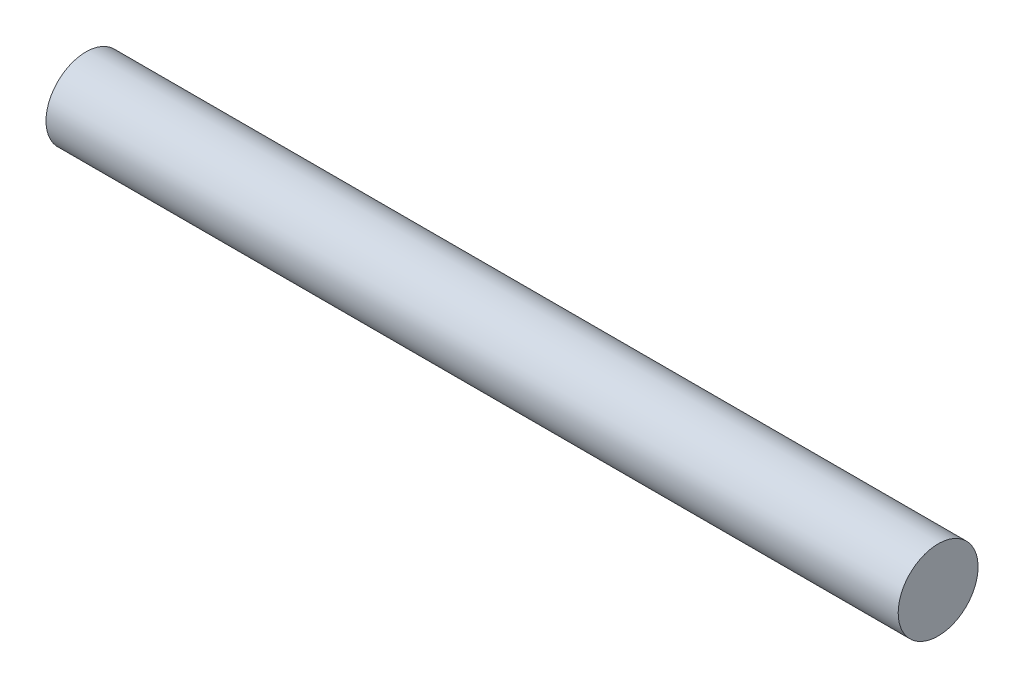
SolidWorks part; units mm, degrees
material "Brass"
ref_plane "Front Plane" through (0, 0, 0) normal (0, 0, 1) x (1, 0, 0)
ref_plane "Top Plane" through (0, 0, 0) normal (0, 1, 0) x (1, 0, 0)
ref_plane "Right Plane" through (0, 0, 0) normal (1, 0, 0) x (0, 0, -1)
sketch "Sketch1" plane through (0, 0, 0) normal (0, 0, 1) x (1, 0, 0)
  line L1 (-16, -0.75) -> (16, -0.75)
  line L2 (-16, -0.75) -> (-16, 0.75)
  line L3 (-16, 0.75) -> (16, 0.75)
  line L4 (16, -0.75) -> (16, 0.75)
  line L5 (-16, -0.75) -> (16, 0.75) construction
  line L6 (-16, 0.75) -> (16, -0.75) construction
  point P0 (0, 0)
  dimension "D1" = 1.5
  dimension "D2" = 32
revolve "Revolve1" add sketch "Sketch1" angle 360 about L1
